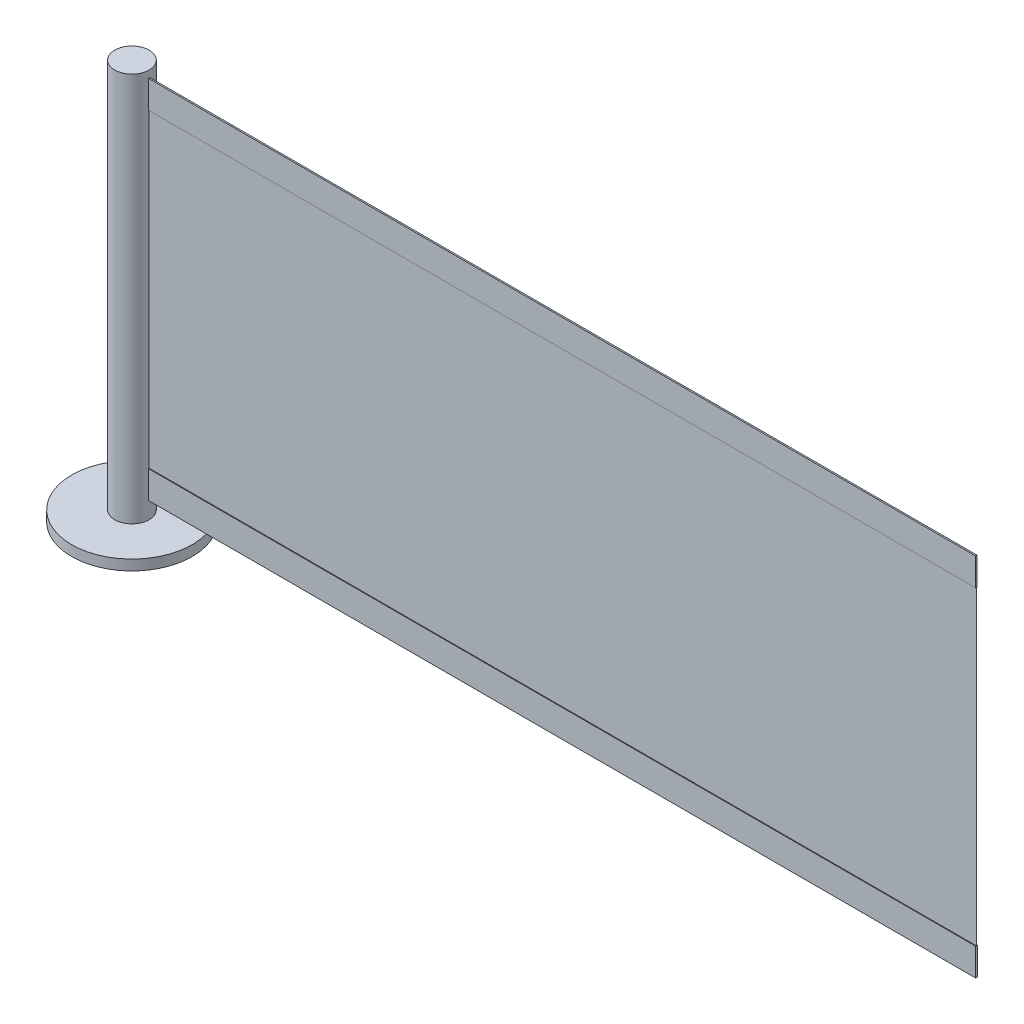
SolidWorks part; units mm, degrees
ref_plane "Front Plane" through (0, 0, 0) normal (0, 0, 1) x (1, 0, 0)
ref_plane "Top Plane" through (0, 0, 0) normal (0, 1, 0) x (1, 0, 0)
ref_plane "Right Plane" through (0, 0, 0) normal (1, 0, 0) x (0, 0, -1)
sketch "Sketch2" plane through (0, 0, 0) normal (0, 1, 0) x (1, 0, 0)
  circle A0 centre (0, 0) radius 175
extrude "Boss-Extrude1" add sketch "Sketch2" along normal blind 30
sketch "Sketch3" plane through (0, 30, 0) normal (0, 1, 0) x (1, 0, 0)
  circle A1 centre (0, 0) radius 50
extrude "Boss-Extrude2" add sketch "Sketch3" along normal blind 1110
sketch "Sketch7" plane through (0, 1140, 0) normal (0, 1, 0) x (1, 0, 0)
  line L0 (0, -0.5) -> (0, 0.5) construction
  line L2 (0, -0.5) -> (2450, -0.5)
  line L3 (0, -0.5) -> (0, 0.5)
  line L4 (0, 0.5) -> (2450, 0.5)
  line L5 (2450, -0.5) -> (2450, 0.5)
  point P5 (0, 0)
  dimension "D1" = 1
  dimension "D2" = 2450
extrude "Boss-Extrude3" add sketch "Sketch7" against normal blind 1060
sketch "Sketch8" plane through (0, 1140, 0) normal (0, 1, 0) x (1, 0, 0)
  line L0 (0, -2) -> (0, 2) construction
  line L2 (0, -2) -> (2450, -2)
  line L3 (0, -2) -> (0, 2)
  line L4 (0, 2) -> (2450, 2)
  line L5 (2450, -2) -> (2450, 2)
  point P4 (0, 0)
  dimension "D1" = 4
  dimension "D2" = 2450
extrude "Boss-Extrude4" add sketch "Sketch8" against normal blind 80
sketch3d "3DSketch2"
  line L0 (2450, 80, 0.5) -> (2450, 80, -0.5) construction
  line L1 (2450, 80, -0.5) -> (49.9975, 80, -0.5) construction
sketch "Sketch11" plane through (0, 80, 0) normal (0, -1, 0) x (-1, 0, 0)
  line L0 (-2450, -2.4692) -> (-2450, 2.4692) construction
  line L2 (-2450, -0.5) -> (-2450, 0.5) construction
  line L4 (-2450, -2.4692) -> (0, -2.4692)
  line L5 (-2450, -2.4692) -> (-2450, 2.4692)
  line L6 (-2450, 2.4692) -> (0, 2.4692)
  line L7 (0, -2.4692) -> (0, 2.4692)
  point P3 (-2450, 0)
  dimension "D1" = 2450
extrude "Boss-Extrude5" add sketch "Sketch11" against normal blind 80
sketch "Sketch12" plane through (0, 1140, 0) normal (0, 1, 0) x (1, 0, 0)
  circle A0 centre (0, 0) radius 50
extrude "Boss-Extrude6" add sketch "Sketch12" along normal blind 20
